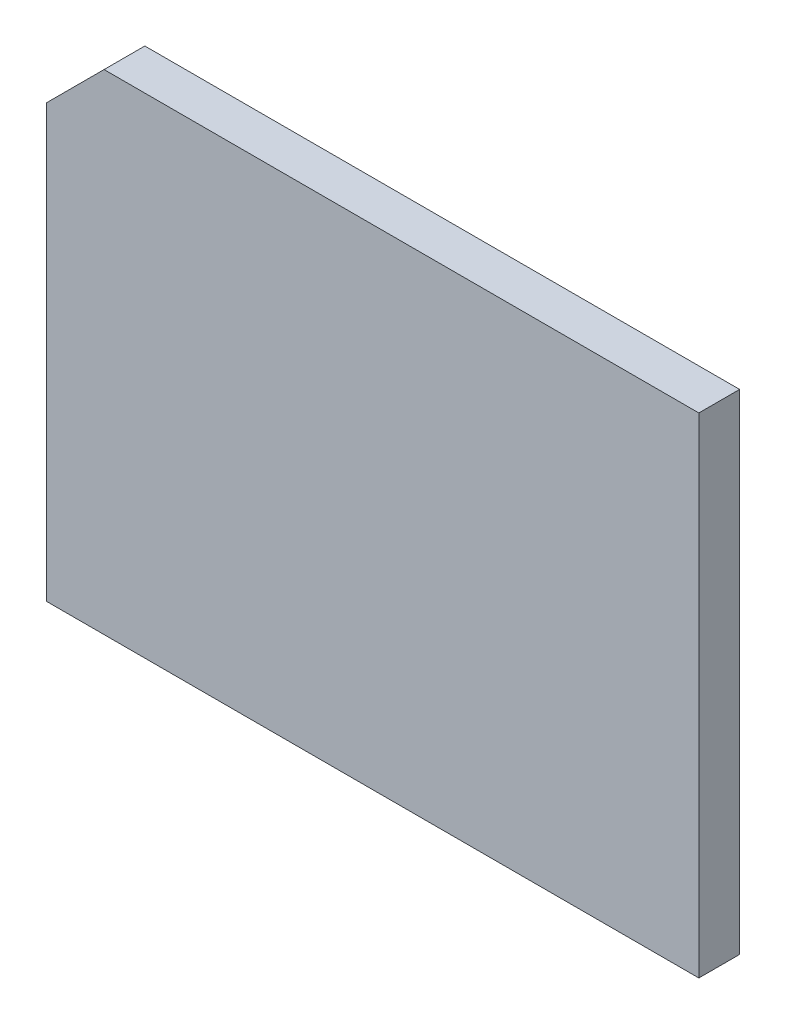
SolidWorks part; units mm, degrees
ref_plane "Front Plane" through (0, 0, 0) normal (0, 0, 1) x (1, 0, 0)
ref_plane "Top Plane" through (0, 0, 0) normal (0, 1, 0) x (1, 0, 0)
ref_plane "Right Plane" through (0, 0, 0) normal (1, 0, 0) x (0, 0, -1)
sketch "Sketch1" plane through (0, 0, 0) normal (0, 0, 1) x (1, 0, 0)
  line L0 (-15.24, 8.7359) -> (-12.5459, 11.43)
  line L1 (-15.24, -11.43) -> (15.24, -11.43)
  line L2 (-15.24, -11.43) -> (-15.24, 8.7359)
  line L3 (-12.5459, 11.43) -> (15.24, 11.43)
  line L4 (15.24, -11.43) -> (15.24, 11.43)
  point P0 (0, 0)
  dimension "D2" = 22.86
  dimension "D3" = 45
  dimension "D4" = 3.81
extrude "Boss-Extrude1" add sketch "Sketch1" along normal blind 1.905
